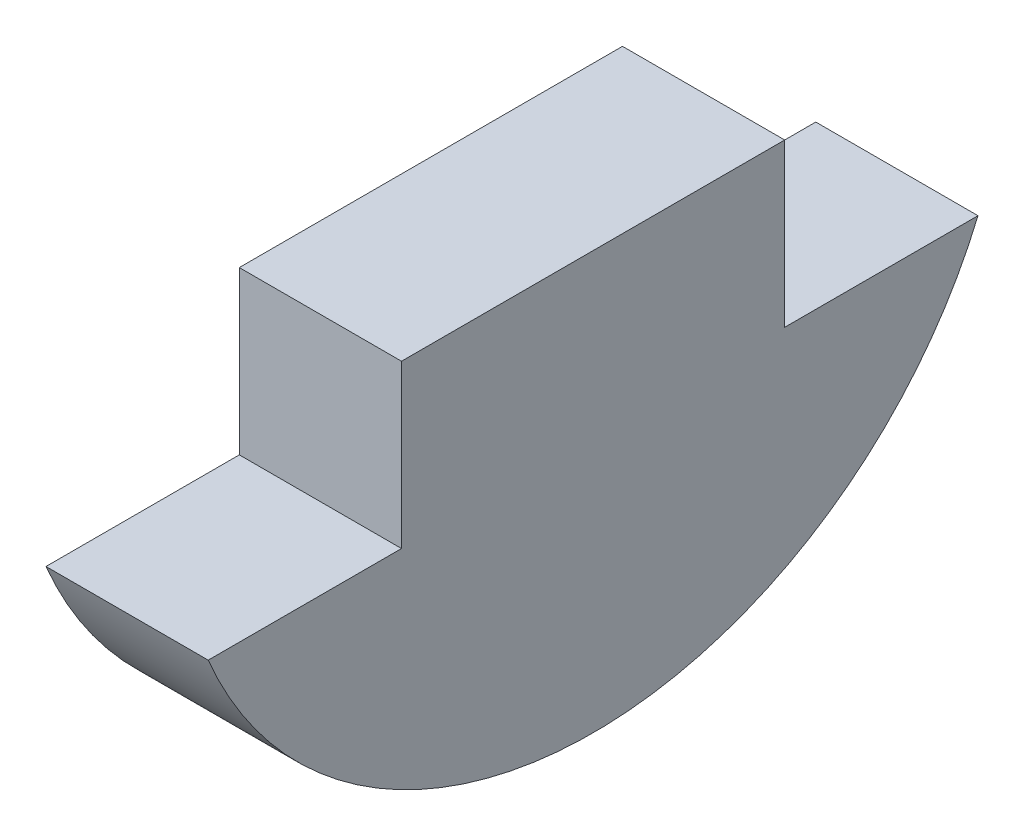
SolidWorks part; units mm, degrees
ref_plane "Front Plane" through (0, 0, 0) normal (0, 0, 1) x (1, 0, 0)
ref_plane "Top Plane" through (0, 0, 0) normal (0, 1, 0) x (1, 0, 0)
ref_plane "Right Plane" through (0, 0, 0) normal (1, 0, 0) x (0, 0, -1)
sketch "Sketch1" plane through (0, 0, 0) normal (1, 0, 0) x (0, 0, -1)
  line L0 (-3, 0) -> (3, 0)
  line L1 (3, 0) -> (3, -2.54)
  line L2 (-3, 0) -> (-3, -2.54)
  line L3 (-3, -2.54) -> (-6.0266, -2.54)
  line L4 (3, -2.54) -> (6.0266, -2.54)
  arc A0 (-6.0266, -2.54) -> (6.0266, -2.54) centre (0, 0) ccw
  point P2 (0, 0)
  dimension "D1" = 6.54
  dimension "D2" = 2.54
  dimension "D3" = 6
extrude "Base" add sketch "Sketch1" along normal blind 2.54
